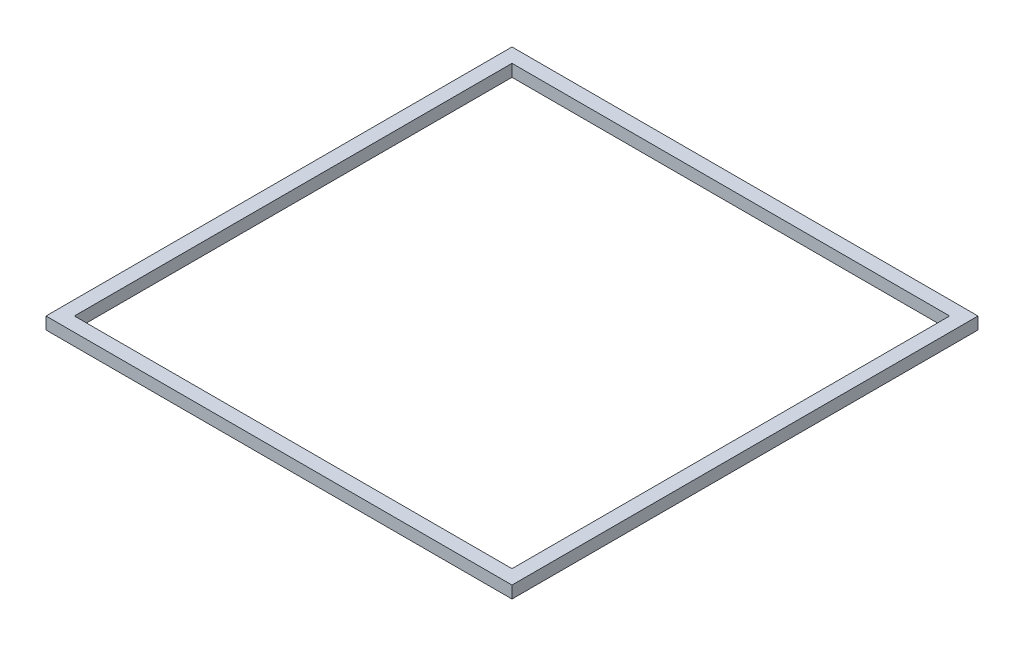
SolidWorks part; units mm, degrees
ref_plane "정면" through (0, 0, 0) normal (0, 0, 1) x (1, 0, 0)
ref_plane "윗면" through (0, 0, 0) normal (0, 1, 0) x (1, 0, 0)
ref_plane "우측면" through (0, 0, 0) normal (1, 0, 0) x (0, 0, -1)
sketch "스케치2" plane through (0, 0, 0) normal (0, 1, 0) x (1, 0, 0)
  line L1 (-57.5, -57.5) -> (57.5, -57.5)
  line L2 (-57.5, -57.5) -> (-57.5, 57.5)
  line L3 (-57.5, 57.5) -> (57.5, 57.5)
  line L4 (57.5, -57.5) -> (57.5, 57.5)
  line L5 (-57.5, -57.5) -> (57.5, 57.5) construction
  line L6 (-57.5, 57.5) -> (57.5, -57.5) construction
  line L7 (-54, -54) -> (54, -54)
  line L8 (-54, -54) -> (-54, 54)
  line L9 (-54, 54) -> (54, 54)
  line L10 (54, -54) -> (54, 54)
  line L11 (-54, -54) -> (54, 54) construction
  line L12 (-54, 54) -> (54, -54) construction
  point P0 (0, 0)
  point P6 (0, 0)
  dimension "D1" = 115
  dimension "D2" = 115
  dimension "D3" = 108
  dimension "D4" = 108
extrude "보스-돌출2" add sketch "스케치2" along normal blind 3
